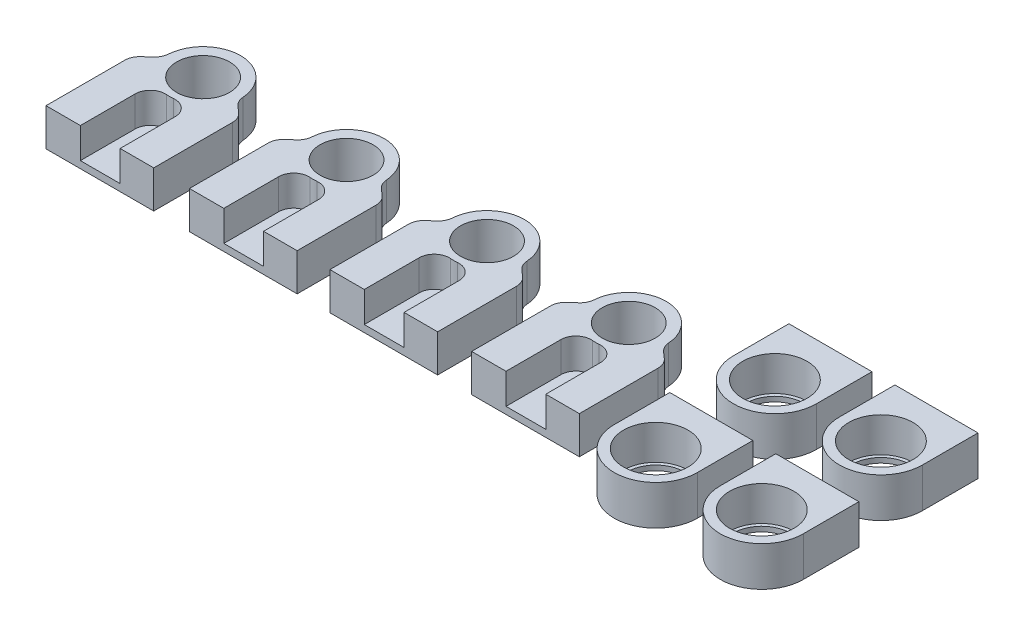
SolidWorks part; units mm, degrees
material "6061-T6 (SS)"
ref_plane "Front Plane" through (0, 0, 0) normal (0, 0, 1) x (1, 0, 0)
ref_plane "Top Plane" through (0, 0, 0) normal (0, 1, 0) x (1, 0, 0)
ref_plane "Right Plane" through (0, 0, 0) normal (1, 0, 0) x (0, 0, -1)
sketch "Sketch1" plane through (0, 0, 0) normal (0, 1, 0) x (1, 0, 0)
  line L5 (-8, -17.9925) -> (0, -11.9925) construction
  line L6 (-13.2136, -2.0823) -> (0, -11.9925) construction
  line L7 (-11.9925, 0) -> (-11.9925, -1)
  line L8 (-14.75, -7.2925) -> (-8.75, -7.2925) construction
  line L9 (-8.75, -7.2925) -> (-8.75, -11.2925) construction
  line L10 (-8.75, -11.2925) -> (-8.75, -17.9925) construction
  line L11 (-11.9925, -1) -> (-17.2732, -5.6802)
  line L12 (-16, -17.9925) -> (16, -17.9925)
  line L13 (0, -17.9925) -> (0, 17.0541) construction
  line L14 (14.75, -7.2925) -> (14.75, -17.9925) construction
  line L15 (-14.75, -7.2925) -> (-14.75, -17.9925) construction
  line L17 (-17.2732, -5.6802) -> (-17.2732, -17.9925)
  line L18 (-17.2732, -17.9925) -> (-16, -17.9925)
  line L19 (8.75, -11.2925) -> (8.75, -17.9925) construction
  line L20 (8.75, -7.2925) -> (8.75, -11.2925) construction
  line L21 (14.75, -7.2925) -> (8.75, -7.2925) construction
  line L22 (13.2136, -2.0823) -> (0, -11.9925) construction
  line L23 (8, -17.9925) -> (0, -11.9925) construction
  line L24 (17.2732, -17.9925) -> (16, -17.9925)
  line L25 (17.2732, -5.6802) -> (17.2732, -17.9925)
  line L26 (11.9925, -1) -> (17.2732, -5.6802)
  line L27 (11.9925, 0) -> (11.9925, -1)
  circle A0 centre (0, 0) radius 8.4925
  arc A1 (11.9925, 0) -> (-11.9925, 0) centre (0, 0) ccw
  circle A3 centre (0, 0) radius 11.9925 construction
  circle A4 centre (0, 0) radius 8.4925 construction
  point P5 (0, -11.9925)
  dimension "D1" = 16.985
  dimension "D2" = 3.5
extrude "Boss-Extrude1" add sketch "Sketch1" along normal blind 12
sketch "Sketch2" plane through (0, 0, 17.9925) normal (0, 0, 1) x (1, 0, 0)
  line L0 (-17.2732, 12) -> (-11.8114, 12) construction
  line L1 (-17.2732, 12) -> (17.2732, 12) construction
  line L2 (-11.8114, 12) -> (-11.8114, 6) construction
  line L3 (17.2732, 12) -> (11.8114, 12) construction
  line L4 (11.8114, 12) -> (11.8114, 6) construction
  circle A0 centre (-11.8114, 6) radius 2.5
  circle A1 centre (11.8114, 6) radius 2.5
extrude "Cut-Extrude1" cut sketch "Sketch2" against normal blind 10.5
sketch "Sketch3" plane through (0, 12, 0) normal (0, 1, 0) x (1, 0, 0)
  line L0 (-9.3114, -17.9925) -> (-6.25, -17.9925) construction
  line L1 (-17.2732, -17.9925) -> (17.2732, -17.9925) construction
  line L2 (-6.25, -17.9925) -> (-6.25, -8.7372)
  line L3 (9.3114, -17.9925) -> (6.5, -17.9925) construction
  line L4 (6.5, -17.9925) -> (6.5, -8.5529)
  line L5 (-6.25, -17.9925) -> (6.5, -17.9925)
  circle A3 centre (0, 0) radius 10.7425
  arc A4 (-6.25, -8.7372) -> (6.5, -8.5529) centre (0, 0) ccw
  dimension "D1" = 2.25
extrude "Cut-Extrude2" cut sketch "Sketch3" against normal blind 20
fillet "Fillet1" radius 4.85 6 edges at (6.5, 6, 8.5529) (-6.25, 6, 8.7372) (-17.2732, 6, 5.6802) (-11.9925, 6, 1) (11.9925, 6, 1) (17.2732, 6, 5.6802)
sketch "Sketch4" plane through (0, 0, 17.9925) normal (0, 0, 1) x (1, 0, 0)
  line L30 (6.5, 12) -> (6.5, 0)
  line L31 (6.5, 0) -> (14.8114, 0)
  line L32 (17.2732, 2.5) -> (17.2732, 9.5)
  line L33 (14.8114, 12) -> (6.5, 12)
  line L53 (-14.8114, 0) -> (-6.25, 0)
  line L54 (-17.2732, 9.5) -> (-17.2732, 2.5)
  line L55 (-6.25, 0) -> (-6.25, 12)
  line L56 (-6.25, 12) -> (-14.8114, 12)
  line L61 (-17.2732, 9.5) -> (-17.2732, 12)
  line L62 (-17.2732, 12) -> (-14.8114, 12)
  line L63 (-14.8114, 0) -> (-17.2732, 0)
  line L64 (-17.2732, 0) -> (-17.2732, 2.5)
  line L65 (14.8114, 12) -> (17.2732, 12)
  line L66 (17.2732, 12) -> (17.2732, 9.5)
  line L67 (14.8114, 0) -> (17.2732, 0)
  line L68 (17.2732, 0) -> (17.2732, 2.5)
  circle A29 centre (-11.8114, 6) radius 2.5
  circle A32 centre (11.8114, 6) radius 2.5
extrude "Boss-Extrude2" add sketch "Sketch4" along normal blind 15.12
sketch "Sketch5" plane through (0, 0, 0) normal (0, -1, 0) x (1, 0, 0)
  line L6 (-6.25, 33.1125) -> (6.5, 33.1125)
  line L8 (6.5, 33.1125) -> (6.5, 15.505)
  line L9 (-6.25, 15.5295) -> (-6.25, 33.1125)
  line L10 (6.5, 33.1125) -> (6.5, 15.505)
  line L11 (-6.25, 15.5295) -> (-6.25, 33.1125)
  arc A12 (1.1368, 10.6822) -> (6.5, 15.505) centre (1.65, 15.505) ccw
  arc A13 (1.1368, 10.6822) -> (-0.9645, 10.6991) centre (0, 0) ccw
  arc A14 (-6.25, 15.5295) -> (-0.9645, 10.6991) centre (-1.4, 15.5295) ccw
  arc A15 (1.1368, 10.6822) -> (6.5, 15.505) centre (1.65, 15.505) ccw
  arc A16 (1.1368, 10.6822) -> (-0.9645, 10.6991) centre (0, 0) ccw
  arc A17 (-6.25, 15.5295) -> (-0.9645, 10.6991) centre (-1.4, 15.5295) ccw
  dimension "D1" = 0
extrude "Boss-Extrude3" add sketch "Sketch5" against normal blind 2.25 separate body
combine bodies "Combine1" operation type add bodies to combine 105 104
sketch "Sketch6" plane through (0, 0, 33.1125) normal (0, 0, 1) x (1, 0, 0)
  circle A0 centre (-11.5522, 5.8733) radius 3.7643
  circle A1 centre (11.6608, 5.5835) radius 3.8222
extrude "Boss-Extrude4" add sketch "Sketch6" against normal blind 28
move or copy body "Body-Move/Copy1" bodies to move or copy 107 copy yes number of copies 1 translate (45.0508, 0, 0)
move or copy body "Body-Move/Copy2" bodies to move or copy 108 copy yes number of copies 1 translate (45.4485, 0, 0)
sketch "Sketch7" plane through (0, 0, 0) normal (0, 1, 0) x (1, 0, 0)
  line L5 (114.6177, 6.9345) -> (114.6177, 20.2532)
  line L6 (141.2552, 20.2532) -> (141.2552, 6.9345)
  line L7 (114.6177, 20.2532) -> (114.6177, 24.7532)
  line L8 (114.6177, 24.7532) -> (141.2552, 24.7532)
  line L9 (141.2552, 24.7532) -> (141.2552, 20.2532)
  arc A2 (114.6177, 6.9345) -> (141.2552, 6.9345) centre (127.9365, 6.9345) ccw
  circle A3 centre (127.9365, 6.9345) radius 9.25
extrude "Boss-Extrude5" add sketch "Sketch7" along normal blind 12.7 separate body
sketch "Sketch9" plane through (0, 12.7, 0) normal (0, 1, 0) x (1, 0, 0)
  circle A0 centre (127.9365, 6.9345) radius 10.3125
  dimension "D1" = 20.625
extrude "Cut-Extrude3" cut sketch "Sketch9" against normal blind 11.11
move or copy body "Body-Move/Copy3" bodies to move or copy 111 copy yes number of copies 1 translate (0, 0, 38.2042)
move or copy body "Body-Move/Copy4" bodies to move or copy 112 copy yes number of copies 1 translate (34, 0, 0)
move or copy body "Body-Move/Copy5" bodies to move or copy 111 copy yes number of copies 1 translate (34, 0, 0)
move or copy body "Body-Move/Copy6" bodies to move or copy 114 112 113 111 copy no translate (2.5, 0, 0)
move or copy body "Body-Move/Copy7" bodies to move or copy 107 copy yes number of copies 1 translate (-46, 0, 0)
